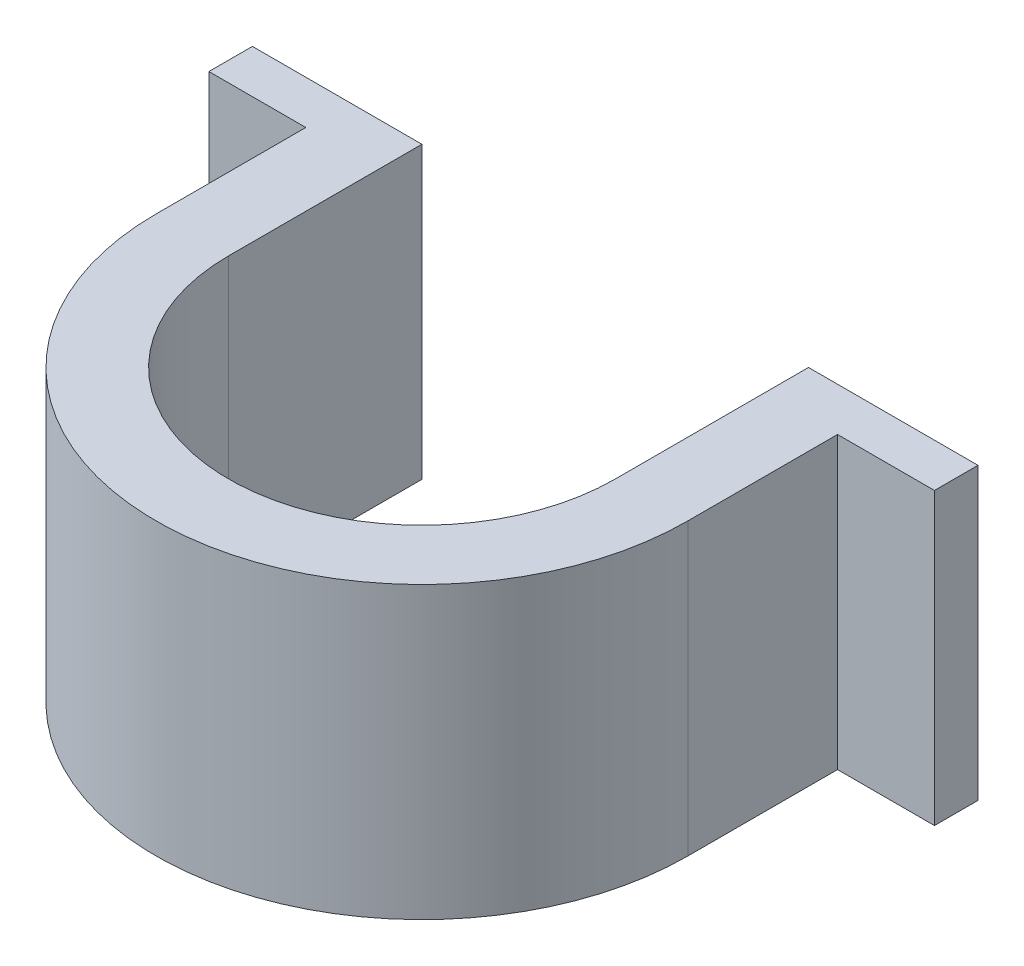
SolidWorks part; units mm, degrees
ref_plane "Front Plane" through (0, 0, 0) normal (0, 0, 1) x (1, 0, 0)
ref_plane "Top Plane" through (0, 0, 0) normal (0, 1, 0) x (1, 0, 0)
ref_plane "Right Plane" through (0, 0, 0) normal (1, 0, 0) x (0, 0, -1)
sketch "Sketch1" plane through (0, 0, 0) normal (0, 1, 0) x (1, 0, 0)
  line L0 (-13.32, 0) -> (-13.32, 13.32)
  line L1 (-13.32, 13.32) -> (-25, 13.32)
  line L2 (-25, 13.32) -> (-25, 10.32)
  line L3 (-25, 10.32) -> (-18.32, 10.32)
  line L4 (-18.32, 10.32) -> (-18.32, 2.0756)
  line L5 (13.32, 0) -> (13.32, 13.32)
  line L6 (13.32, 13.32) -> (25, 13.32)
  line L7 (25, 13.32) -> (25, 10.32)
  line L8 (25, 10.32) -> (18.32, 10.32)
  line L9 (18.32, 10.32) -> (18.32, 1.6853)
  line L10 (-18.32, 2.0756) -> (-18.32, 2.0756)
  line L11 (-18.32, 2.0756) -> (-18.32, 2.0756)
  line L12 (-18.32, 2.0756) -> (-18.32, 2.0756)
  line L13 (-18.32, 2.0756) -> (-18.32, 2.0756)
  line L14 (-18.32, 0) -> (-18.32, 2.0756)
  line L15 (18.32, 0) -> (18.32, 1.6853)
  line L16 (18.32, 1.6853) -> (18.32, 1.6853)
  line L17 (18.32, 1.6853) -> (18.32, 1.6853)
  line L18 (18.32, 1.6853) -> (18.32, 1.6853)
  line L19 (18.32, 1.6853) -> (18.32, 1.6853)
  line L20 (18.32, 10.32) -> (18.32, 6.6853) construction
  line L21 (-18.32, 10.32) -> (-18.32, 7.0756) construction
  line L22 (0, 0) -> (0, 16.091) construction
  arc A0 (-13.32, 0) -> (13.32, 0) centre (0, 0) ccw
  arc A1 (-18.32, 0) -> (18.32, 0) centre (0, 0) ccw
  point P14 (0, -13.32)
  dimension "D1" = 13.32
  dimension "D2" = 26.64
  dimension "D4" = 50
  dimension "D5" = 3
  dimension "D6" = 3
  dimension "D3" = 5
extrude "Boss-Extrude1" add sketch "Sketch1" along normal blind 20 contours L14 A1 L15 L9 L8 L7 L6 L5 A0 L0 L1 L2 L3 L4
